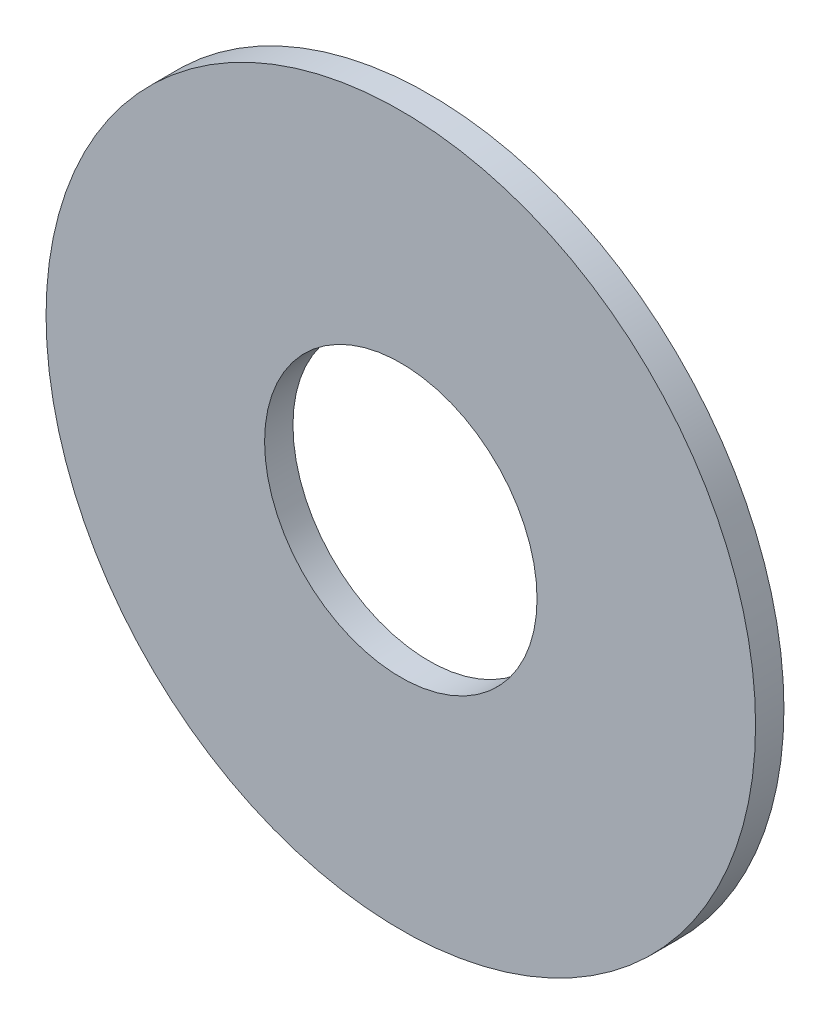
SolidWorks part; units mm, degrees
ref_plane "Plane1" through (0, 0, 0) normal (0, 0, 1) x (1, 0, 0)
ref_plane "Plane2" through (0, 0, 0) normal (0, 1, 0) x (1, 0, 0)
ref_plane "Plane3" through (0, 0, 0) normal (1, 0, 0) x (0, 0, -1)
other "Configuration Table"
sketch "Sketch1" plane through (0, 0, 0) normal (0, 0, 1) x (1, 0, 0)
  circle A0 centre (0, 0) radius 6.25
  circle A1 centre (0, 0) radius 2.4
  dimension "D1" = 4.8
  dimension "D2" = 12.5
extrude "shaft washers" add sketch "Sketch1" along normal blind 0.5
